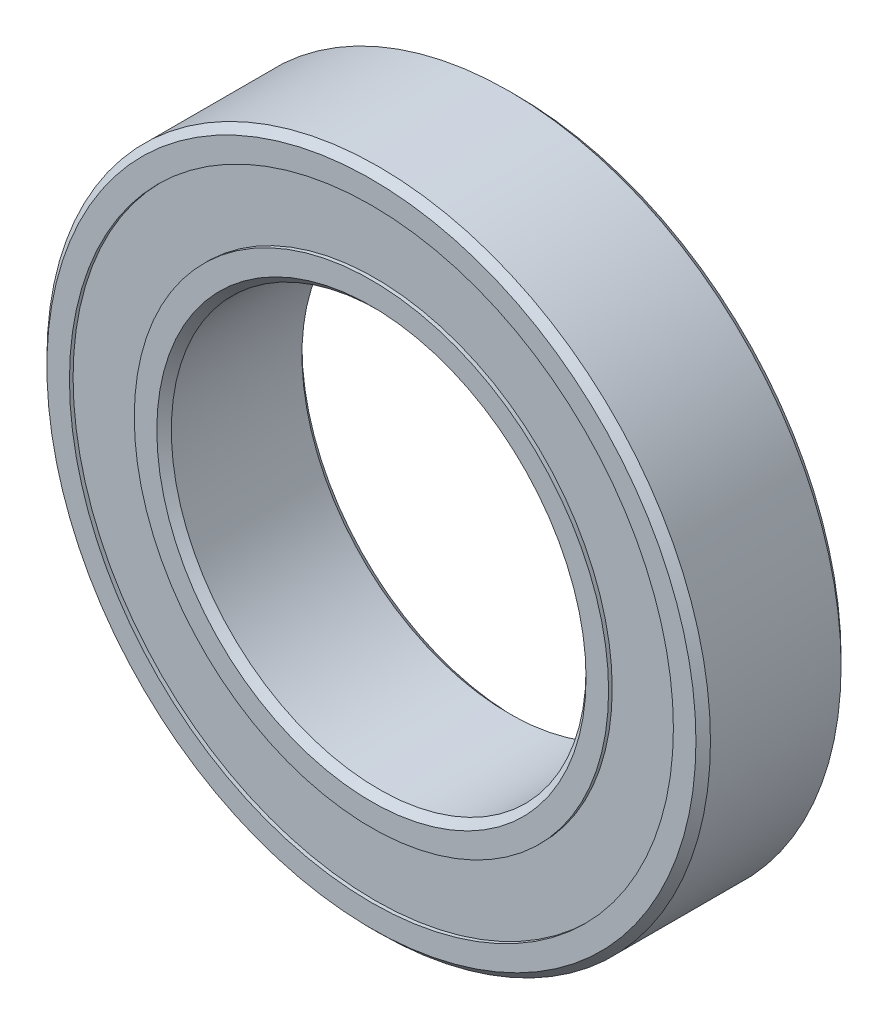
SolidWorks part; units mm, degrees
ref_plane "Front Plane" through (0, 0, 0) normal (0, 0, 1) x (1, 0, 0)
ref_plane "Top Plane" through (0, 0, 0) normal (0, 1, 0) x (1, 0, 0)
ref_plane "Right Plane" through (0, 0, 0) normal (1, 0, 0) x (0, 0, -1)
sketch "Sketch1" plane through (0, 0, 0) normal (0, 0, 1) x (1, 0, 0)
  circle A0 centre (0, 0) radius 16 construction
  circle A1 centre (0, 0) radius 10 construction
  dimension "OD" = 32
  dimension "ID" = 20
sketch "Sketch2" plane through (0, 0, 0) normal (1, 0, 0) x (0, 0, -1)
  line L0 (-3.5, 0) -> (3.5, 0) construction
  line L1 (0, 16) -> (0, -16) construction
  line L2 (3.15, 16) -> (-3.15, 16) construction
  line L3 (-3.15, 16) -> (-3.5, 15.65) construction
  line L4 (-3.5, 15.65) -> (-3.5, 14.5625) construction
  line L5 (-3.5, 14.5625) -> (-1.5556, 14.5625) construction
  line L6 (3.5, 14.5625) -> (1.5556, 14.5625) construction
  line L7 (3.5, 15.65) -> (3.5, 14.5625) construction
  line L8 (3.15, 16) -> (3.5, 15.65) construction
  line L9 (0, 16) -> (0, 13) construction
  line L10 (0, 13) -> (0, 10) construction
  line L11 (3.5, 13) -> (-3.5, 13) construction
  line L12 (-3.5, 10.35) -> (-3.5, 11.4375) construction
  line L13 (-3.15, 10) -> (-3.5, 10.35) construction
  line L14 (3.15, 10) -> (-3.15, 10) construction
  line L15 (3.15, 10) -> (3.5, 10.35) construction
  line L16 (3.5, 10.35) -> (3.5, 11.4375) construction
  line L17 (3.5, 11.4375) -> (1.5556, 11.4375) construction
  line L18 (-3.5, 11.4375) -> (-1.5556, 11.4375) construction
  line L19 (-3.5, 10) -> (-3.5, -10) construction
  line L20 (3.5, 16) -> (3.5, -16) construction
  arc A0 (-1.5556, 14.5625) -> (1.5556, 14.5625) centre (0, 13) cw construction
  arc A1 (-1.5556, 11.4375) -> (1.5556, 11.4375) centre (0, 13) ccw construction
  point P14 (0, 10)
  point P18 (0, 13)
  dimension "Approx. Ball Dia." = 4.4096
  dimension "D1" = 45
  dimension "D2" = 0.35
  dimension "D3" = 3.1111
  dimension "D4" = 1.5625
  dimension "Width" = 7
  dimension "For Shaft Diameter" = 20
  dimension "For Housing ID" = 32
sketch "Sketch3" plane through (0, 0, 0) normal (1, 0, 0) x (0, 0, -1)
  line L0 (-3.5, 15.65) -> (-3.5, 14.5625) construction
  line L1 (-3.15, 16) -> (-3.5, 15.65) construction
  line L2 (3.15, 16) -> (-3.15, 16) construction
  line L3 (3.15, 16) -> (3.5, 15.65) construction
  line L4 (3.5, 15.65) -> (3.5, 14.5625) construction
  line L5 (3.5, 14.5625) -> (1.5556, 14.5625) construction
  line L6 (-3.5, 14.5625) -> (-1.5556, 14.5625) construction
  line L7 (-3.5, 15.65) -> (-3.5, 14.5625)
  line L8 (-3.15, 16) -> (-3.5, 15.65)
  line L9 (3.15, 16) -> (-3.15, 16)
  line L10 (3.15, 16) -> (3.5, 15.65)
  line L11 (3.5, 15.65) -> (3.5, 14.5625)
  line L12 (3.5, 14.5625) -> (1.5556, 14.5625)
  line L13 (-3.5, 14.5625) -> (-1.5556, 14.5625)
  line L14 (-3.5, 10.35) -> (-3.5, 11.4375) construction
  line L15 (-3.15, 10) -> (-3.5, 10.35) construction
  line L16 (3.15, 10) -> (-3.15, 10) construction
  line L17 (3.15, 10) -> (3.5, 10.35) construction
  line L18 (3.5, 10.35) -> (3.5, 11.4375) construction
  line L19 (3.5, 11.4375) -> (1.5556, 11.4375) construction
  line L20 (-3.5, 11.4375) -> (-1.5556, 11.4375) construction
  line L21 (-3.5, 10.35) -> (-3.5, 11.4375)
  line L22 (-3.15, 10) -> (-3.5, 10.35)
  line L23 (3.15, 10) -> (-3.15, 10)
  line L24 (3.15, 10) -> (3.5, 10.35)
  line L25 (3.5, 10.35) -> (3.5, 11.4375)
  line L26 (3.5, 11.4375) -> (1.5556, 11.4375)
  line L27 (-3.5, 11.4375) -> (-1.5556, 11.4375)
  arc A0 (1.5556, 14.5625) -> (-1.5556, 14.5625) centre (0, 13) ccw construction
  arc A1 (1.5556, 14.5625) -> (-1.5556, 14.5625) centre (0, 13) ccw
  arc A2 (-1.5556, 11.4375) -> (1.5556, 11.4375) centre (0, 13) ccw construction
  arc A3 (-1.5556, 11.4375) -> (1.5556, 11.4375) centre (0, 13) ccw
revolve "Revolve1" add sketch "Sketch3" angle 360 about L0
sketch "Sketch4" plane through (0, 0, 0) normal (1, 0, 0) x (0, 0, -1)
  line L0 (-2.2048, 13) -> (2.2048, 13)
  arc A2 (-2.2048, 13) -> (2.2048, 13) centre (0, 13) cw
  arc A3 (1.5556, 14.5625) -> (-1.5556, 14.5625) centre (0, 13) ccw construction
revolve "Revolve2" add sketch "Sketch4" angle 360 about L0
pattern_circular "CirPattern1" count 11 over 360 about axis through (0, 0, 0) along (0, 0, 1) of bodies 104
sketch "Sketch5" plane through (0, 0, 0) normal (1, 0, 0) x (0, 0, -1)
  line L0 (-3.5, 14.5625) -> (-1.5556, 14.5625) construction
  line L1 (-3.325, 14.5625) -> (-2.2048, 14.5625)
  line L2 (-3.325, 14.5625) -> (-3.325, 11.4375)
  line L3 (-3.325, 11.4375) -> (-2.2048, 11.4375)
  line L4 (-2.2048, 14.5625) -> (-2.2048, 11.4375)
  line L6 (3.5, 14.5625) -> (1.5556, 14.5625) construction
  line L7 (3.325, 14.5625) -> (2.2048, 14.5625)
  line L8 (3.325, 14.5625) -> (3.325, 11.4375)
  line L9 (3.325, 11.4375) -> (2.2048, 11.4375)
  line L10 (2.2048, 14.5625) -> (2.2048, 11.4375)
  line L12 (-3.15, 16) -> (-3.5, 15.65) construction
  line L13 (-3.5, 11.4375) -> (-1.5556, 11.4375) construction
  line L14 (3.5, 11.4375) -> (1.5556, 11.4375) construction
  point P18 (-3.325, 15.825)
revolve "Revolve3" add sketch "Sketch5" angle 360 about L0
equation "\"D2@Sketch2\"= \"Width@Sketch2\" * .05"
equation "\"D3@Sketch2\"=\"Width@Sketch2\" / 2.25"
equation "\"D4@Sketch2\"=( \"OD@Sketch1\" - \"Width@Sketch2\" ) *.5 *.125"
equation "\"Approx. No. of Balls\"= ( pi * \"OD@Sketch1\" ) * .5 / \"Approx. Ball Dia.@Sketch2\""
equation "\"Balls@CirPattern1\"=\"Approx. No. of Balls\""
